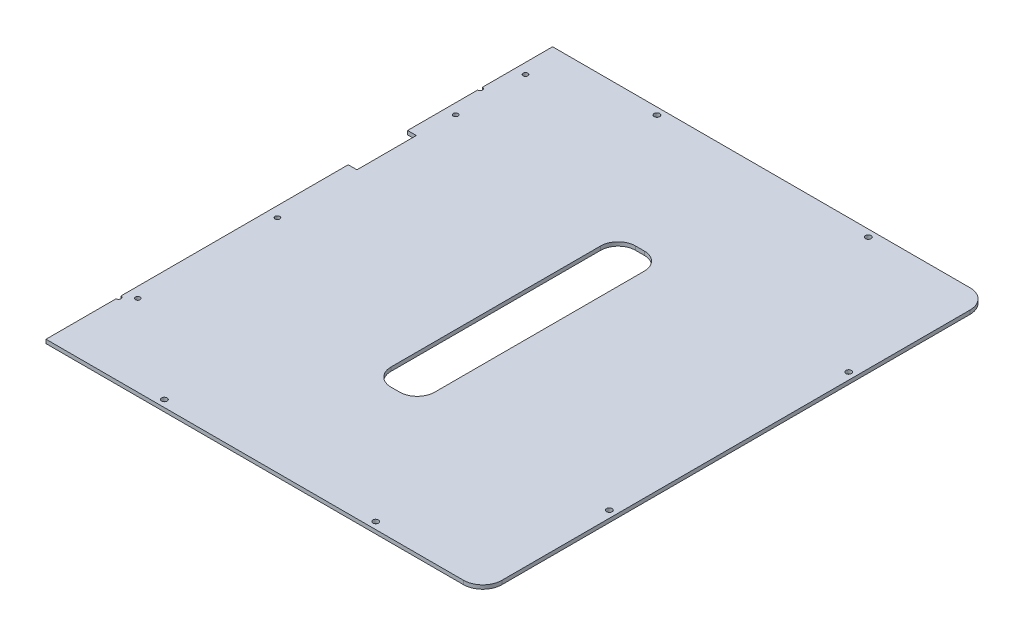
SolidWorks part; units mm, degrees
ref_plane "Front Plane" through (0, 0, 0) normal (0, 0, 1) x (1, 0, 0)
ref_plane "Top Plane" through (0, 0, 0) normal (0, 1, 0) x (1, 0, 0)
ref_plane "Right Plane" through (0, 0, 0) normal (1, 0, 0) x (0, 0, -1)
sketch "Sketch1" plane through (0, 0, 0) normal (0, 1, 0) x (1, 0, 0)
  line L0 (0, 145) -> (0, 141) construction
  line L1 (-239, 145) -> (239, 145)
  line L2 (-250, 134) -> (-250, -134)
  line L3 (-239, -145) -> (239, -145)
  line L4 (250, 134) -> (250, -134)
  line L5 (-250, 145) -> (250, -145) construction
  line L6 (-250, -145) -> (250, 145) construction
  line L7 (0, 0) -> (0, 79.598) construction
  line L8 (0, 0) -> (95.4216, 0) construction
  line L9 (-125, 30) -> (-125, -30) construction
  line L10 (-125, -30) -> (125, -30) construction
  line L11 (125, -30) -> (125, 30) construction
  line L12 (0, 62) -> (0, 28) construction
  line L13 (-127.5, -70) -> (-122.5, -70)
  line L14 (-137.5, -60) -> (-137.5, 60)
  line L15 (-127.5, 70) -> (-122.5, 70)
  line L16 (-112.5, -60) -> (-112.5, 60)
  line L17 (-137.5, -70) -> (-112.5, 70) construction
  line L18 (-137.5, 70) -> (-112.5, -70) construction
  line L19 (122.5, -70) -> (127.5, -70)
  line L20 (112.5, -60) -> (112.5, 60)
  line L21 (122.5, 70) -> (127.5, 70)
  line L22 (137.5, -60) -> (137.5, 60)
  line L23 (112.5, -70) -> (137.5, 70) construction
  line L24 (112.5, 70) -> (137.5, -70) construction
  line L25 (-5, 28) -> (5, 28)
  line L26 (-5, 28) -> (-5, 62)
  line L27 (-5, 62) -> (5, 62)
  line L28 (5, 28) -> (5, 62)
  line L29 (-5, 28) -> (5, 62) construction
  line L30 (-5, 62) -> (5, 28) construction
  arc A0 (-250, -134) -> (-239, -145) centre (-239, -134) ccw
  arc A1 (250, -134) -> (239, -145) centre (239, -134) cw
  arc A2 (250, 134) -> (239, 145) centre (239, 134) ccw
  arc A3 (-239, 145) -> (-250, 134) centre (-239, 134) ccw
  circle A4 centre (63.75, 141) radius 1.6
  circle A5 centre (184.75, 141) radius 1.6
  circle A6 centre (246, 68.5) radius 1.6
  circle A7 centre (0, 103.5) radius 1.4
  circle A8 centre (0, -103.5) radius 1.4
  arc A9 (137.5, 60) -> (127.5, 70) centre (127.5, 60) ccw
  arc A10 (122.5, 70) -> (112.5, 60) centre (122.5, 60) ccw
  arc A11 (137.5, -60) -> (127.5, -70) centre (127.5, -60) cw
  arc A12 (112.5, -60) -> (122.5, -70) centre (122.5, -60) ccw
  arc A13 (-112.5, -60) -> (-122.5, -70) centre (-122.5, -60) cw
  arc A14 (-127.5, -70) -> (-137.5, -60) centre (-127.5, -60) cw
  arc A15 (-112.5, 60) -> (-122.5, 70) centre (-122.5, 60) ccw
  arc A16 (-127.5, 70) -> (-137.5, 60) centre (-127.5, 60) ccw
  circle A17 centre (-246, 68.5) radius 1.6
  circle A18 centre (-184.75, 141) radius 1.6
  circle A19 centre (-63.75, 141) radius 1.6
  circle A20 centre (184.75, -141) radius 1.6
  circle A21 centre (246, -68.5) radius 1.6
  circle A22 centre (63.75, -141) radius 1.6
  circle A23 centre (-63.75, -141) radius 1.6
  circle A24 centre (-184.75, -141) radius 1.6
  circle A25 centre (-246, -68.5) radius 1.6
  point P0 (0, 0)
  point P34 (-125, 0)
  point P41 (125, 0)
  point P76 (0, 45)
  dimension "D3" = 11
  dimension "D8" = 10
  dimension "D1" = 290
  dimension "D2" = 500
  dimension "D4" = 140
  dimension "D5" = 140
  dimension "D6" = 25
  dimension "D7" = 25
  dimension "D9" = 10
  dimension "D10" = 34
extrude "Boss-Extrude1" add sketch "Sketch1" along normal blind 2.2
sketch "Sketch2" plane through (0, 2.2, 0) normal (0, 1, 0) x (1, 0, 0)
  line L0 (0, 62) -> (0, 145) construction
  line L1 (5, 62) -> (-5, 62) construction
  line L2 (239, 145) -> (-239, 145) construction
  line L3 (0, 28) -> (0, -145) construction
  line L4 (-5, 28) -> (5, 28) construction
  line L5 (-239, -145) -> (239, -145) construction
  line L7 (-6, -98.5) -> (6, -98.5) construction
  line L8 (-6, -98.5) -> (-6, -18.5) construction
  line L9 (-6, -18.5) -> (6, -18.5) construction
  line L10 (6, -98.5) -> (6, -18.5) construction
  line L11 (-6, -98.5) -> (6, -18.5) construction
  line L12 (-6, -18.5) -> (6, -98.5) construction
  line L13 (-6, 83.5) -> (6, 83.5) construction
  line L14 (-6, 83.5) -> (-6, 123.5) construction
  line L15 (-6, 123.5) -> (6, 123.5) construction
  line L16 (6, 83.5) -> (6, 123.5) construction
  line L17 (-6, 83.5) -> (6, 123.5) construction
  line L18 (-6, 123.5) -> (6, 83.5) construction
  circle A0 centre (-6, -18.5) radius 1.35
  circle A1 centre (6, -18.5) radius 1.35
  circle A2 centre (-6, -98.5) radius 1.35
  circle A3 centre (6, -98.5) radius 1.35
  circle A4 centre (-6, 123.5) radius 1.35
  circle A5 centre (6, 123.5) radius 1.35
  circle A6 centre (-6, 83.5) radius 1.35
  circle A7 centre (6, 83.5) radius 1.35
  point P12 (0, -58.5)
  point P21 (0, 103.5)
  dimension "D1" = 12
  dimension "D2" = 40
extrude "Cut-Extrude1" cut sketch "Sketch2" against normal blind 59.2
sketch "Sketch4" plane through (0, 2.2, 0) normal (0, 1, 0) x (1, 0, 0)
  line L0 (239, 145) -> (-239, 145) construction
  line L1 (0, 145) -> (-292.7148, 145)
  line L2 (0, 145) -> (0, -181.0074)
  line L3 (0, -181.0074) -> (-292.7148, -181.0074)
  line L4 (-292.7148, 145) -> (-292.7148, -181.0074)
  point P6 (-292.7148, -181.0074)
extrude "Cut-Extrude2" cut sketch "Sketch4" against normal up to surface (2.2 mm away) up to face at (-6, 0, -122.15)
